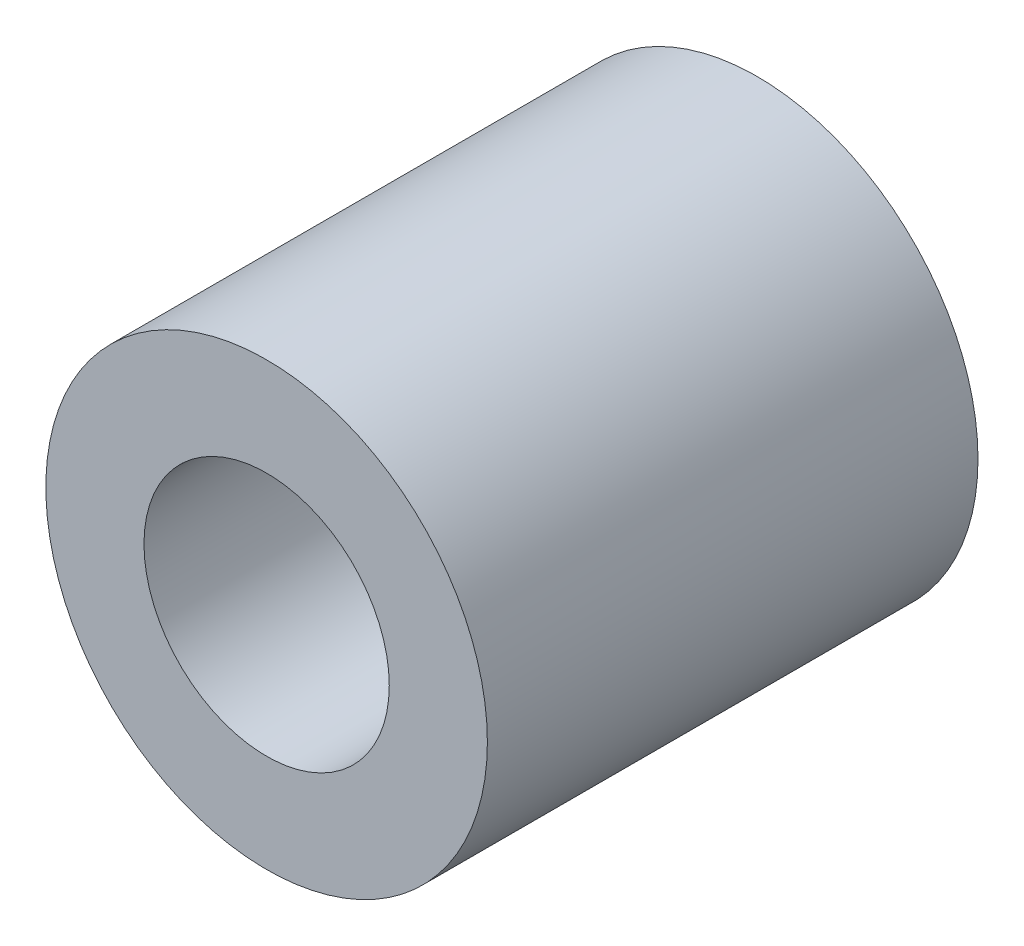
SolidWorks part; units mm, degrees
ref_plane "Front Plane" through (0, 0, 0) normal (0, 0, 1) x (1, 0, 0)
ref_plane "Top Plane" through (0, 0, 0) normal (0, 1, 0) x (1, 0, 0)
ref_plane "Right Plane" through (0, 0, 0) normal (1, 0, 0) x (0, 0, -1)
sketch "Sketch1" plane through (0, 0, 0) normal (0, 0, 1) x (1, 0, 0)
  circle A0 centre (0, 0) radius 4.5
  circle A1 centre (0, 0) radius 2.5
  dimension "D1" = 9
  dimension "D2" = 5
extrude "Boss-Extrude1" add sketch "Sketch1" along normal blind 10
